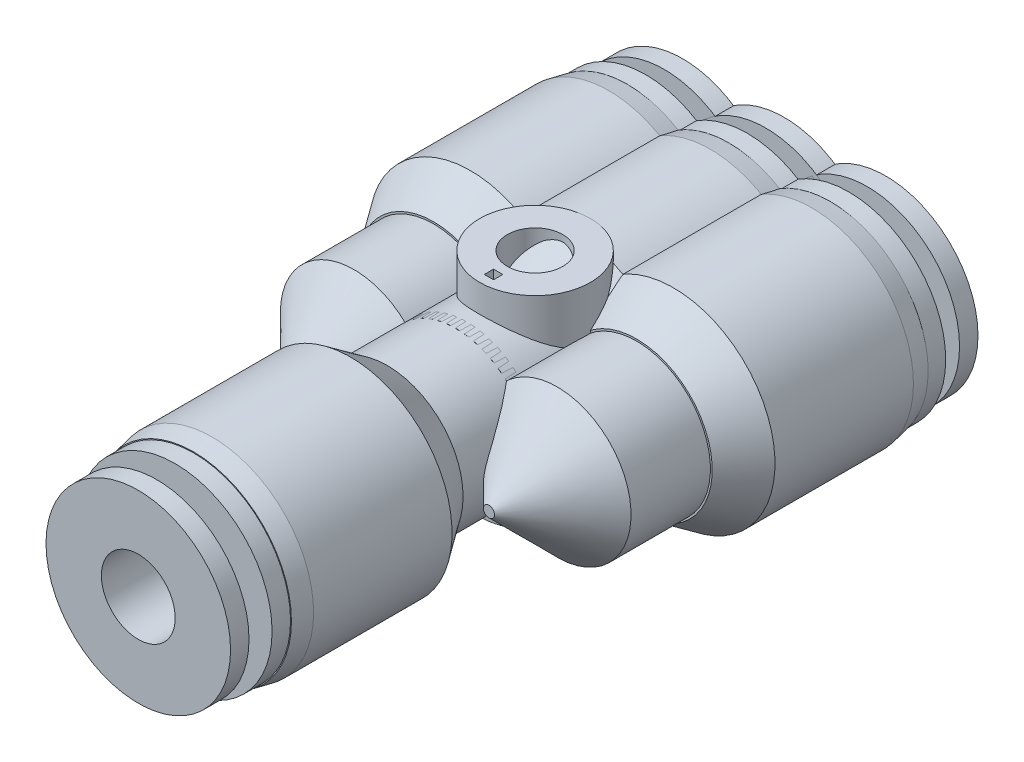
SolidWorks part; units mm, degrees
ref_plane "Front Plane" through (0, 0, 0) normal (0, 0, 1) x (1, 0, 0)
ref_plane "Top Plane" through (0, 0, 0) normal (0, 1, 0) x (1, 0, 0)
ref_plane "Right Plane" through (0, 0, 0) normal (1, 0, 0) x (0, 0, -1)
sketch "Sketch1" plane through (0, 0, 0) normal (0, 0, 1) x (1, 0, 0)
  circle A0 centre (0, 0) radius 5
  dimension "D1" = 10
extrude "Boss-Extrude1" add sketch "Sketch1" along normal blind 1
sketch "Sketch3" plane through (0, 0, 1) normal (0, 0, 1) x (1, 0, 0)
  circle A0 centre (0, 0) radius 3
  dimension "D1" = 6
extrude "Boss-Extrude2" add sketch "Sketch3" along normal blind 1
sketch "Sketch4" plane through (0, 0, 2) normal (0, 0, 1) x (1, 0, 0)
  circle A0 centre (0, 0) radius 5.25
  dimension "D1" = 10.5
extrude "Boss-Extrude3" add sketch "Sketch4" along normal blind 1
sketch "Sketch5" plane through (0, 0, 3) normal (0, 0, 1) x (1, 0, 0)
  circle A0 centre (0, 0) radius 5.5
  dimension "D1" = 11
extrude "Boss-Extrude4" add sketch "Sketch5" along normal blind 10.5
sketch "Sketch6" plane through (0, 0, 13.5) normal (0, 0, 1) x (1, 0, 0)
  circle A0 centre (0, 0) radius 4
  dimension "D1" = 8
extrude "Boss-Extrude5" add sketch "Sketch6" along normal blind 8
chamfer "Chamfer1" distance 0.2 distance2 1 1 edges at (5.5, 0, 3)
chamfer "Chamfer2" distance 2 distance2 1.4 1 edges at (5.5, 0, 13.5)
chamfer "Chamfer3" distance 3.7 angle 45 1 edges at (4, 0, 21.5)
sketch "Sketch7" plane through (0, 0, 0) normal (0, 1, 0) x (1, 0, 0)
  line L0 (0, 0) -> (7.344, 0) construction
sketch "Sketch11" plane through (0, 0, 0) normal (0, 0, -1) x (-1, 0, 0)
  circle A0 centre (0, 0) radius 2
  dimension "D1" = 4
extrude "Cut-Extrude2" cut sketch "Sketch11" against normal blind 10
pattern_linear "LPattern1" count 3 spacing 5.5 along (1, 0, 0) of bodies 114 105
ref_plane "Plane1" through (0, 0, 17.5) normal (0, 0, 1) x (1, 0, 0)
mirror "Mirror1" about plane through (0, 0, 17.5) normal (0, 0, 1) of bodies 106
sketch "Sketch8" plane through (0, 0, 0) normal (0, 1, 0) x (1, 0, 0)
  line L0 (5.8, -13.5) -> (5.2, -13.5) construction
  circle A0 centre (5.5, -13.5) radius 3
  dimension "D1" = 6
extrude "Boss-Extrude7" add sketch "Sketch8" along normal mid plane 11 separate body
sketch "Sketch9" plane through (0, 5.5, 0) normal (0, 1, 0) x (1, 0, 0)
  circle A0 centre (5.5, -13.5) radius 1.5
  dimension "D1" = 3
extrude "Cut-Extrude1" cut sketch "Sketch9" against normal through all
sketch "Sketch12" plane through (0, 5.5, 0) normal (0, 1, 0) x (1, 0, 0)
  line L0 (5.5, -13.5) -> (5.5, -15.75) construction
  line L2 (5.25, -15.5) -> (5.75, -15.5)
  line L3 (5.25, -15.5) -> (5.25, -16)
  line L4 (5.25, -16) -> (5.75, -16)
  line L5 (5.75, -15.5) -> (5.75, -16)
  line L6 (5.25, -15.5) -> (5.75, -16) construction
  line L7 (5.25, -16) -> (5.75, -15.5) construction
  dimension "D1" = 2.25
  dimension "D2" = 0.5
  dimension "D3" = 0.5
extrude "Cut-Extrude3" cut sketch "Sketch12" against normal blind 0.5
